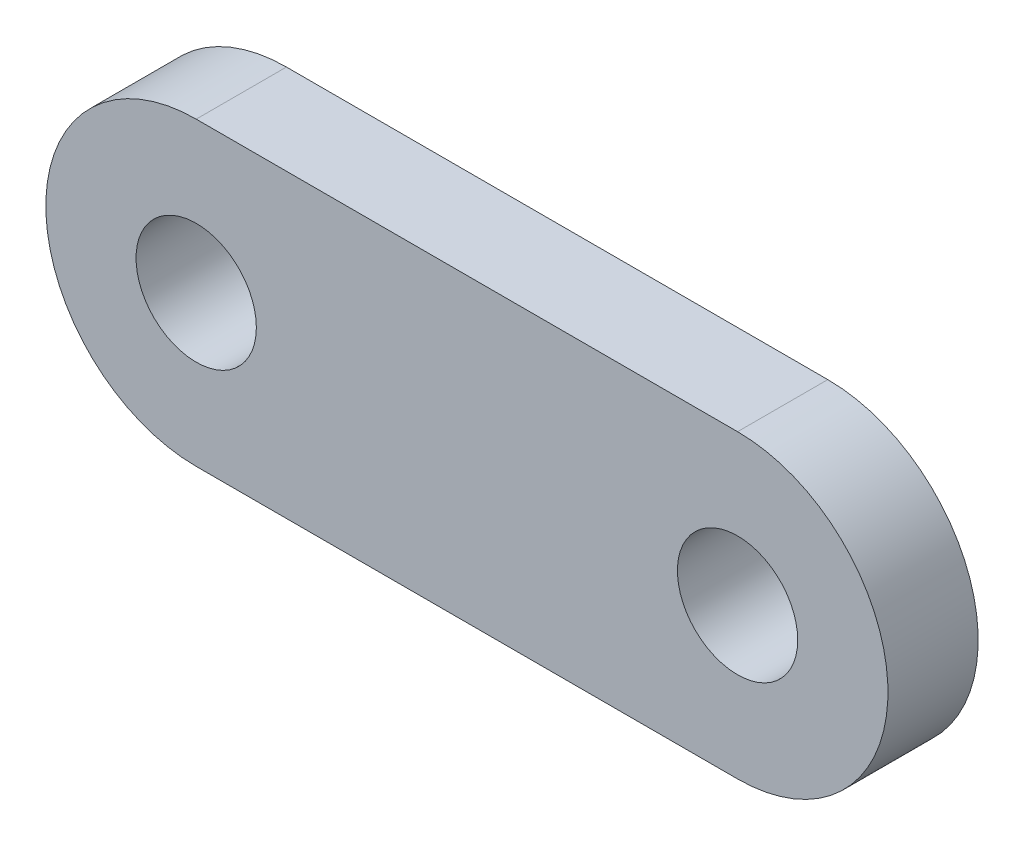
SolidWorks part; units mm, degrees
ref_plane "Front Plane" through (0, 0, 0) normal (0, 0, 1) x (1, 0, 0)
ref_plane "Top Plane" through (0, 0, 0) normal (0, 1, 0) x (1, 0, 0)
ref_plane "Right Plane" through (0, 0, 0) normal (1, 0, 0) x (0, 0, -1)
sketch "Sketch1" plane through (0, 0, 0) normal (0, 0, 1) x (1, 0, 0)
  line L0 (-9, 0) -> (9, 0) construction
  line L1 (-9, 0) -> (9, 0) construction
  line L2 (-9, 5) -> (9, 5)
  line L3 (-9, -5) -> (9, -5)
  circle A0 centre (-9, 0) radius 2
  circle A1 centre (9, 0) radius 2
  arc A2 (-9, 5) -> (-9, -5) centre (-9, 0) ccw
  arc A3 (9, -5) -> (9, 5) centre (9, 0) ccw
  point P4 (0, 0)
  point P6 (0, 0)
  dimension "D2" = 4
  dimension "D3" = 4
  dimension "D1" = 18
  dimension "D4" = 5
extrude "Boss-Extrude1" add sketch "Sketch1" along normal blind 3
